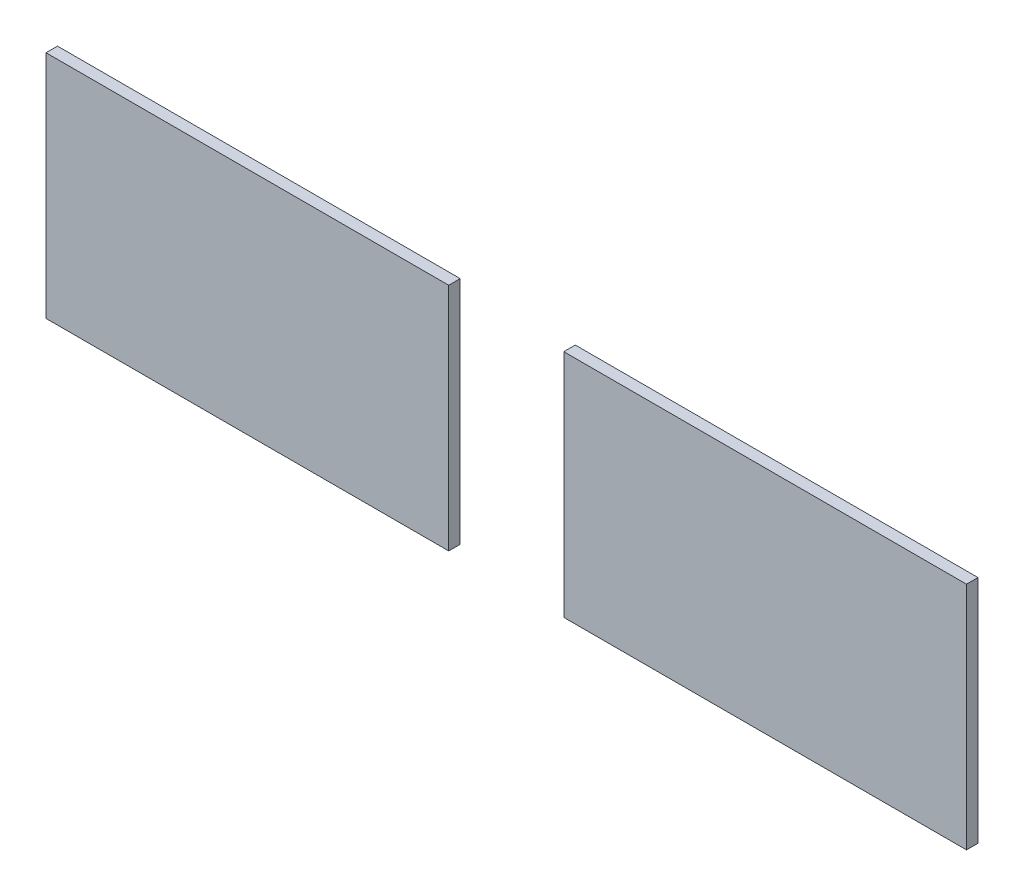
SolidWorks part; units mm, degrees
ref_plane "前视基准面" through (0, 0, 0) normal (0, 0, 1) x (1, 0, 0)
ref_plane "上视基准面" through (0, 0, 0) normal (0, 1, 0) x (1, 0, 0)
ref_plane "右视基准面" through (0, 0, 0) normal (1, 0, 0) x (0, 0, -1)
sketch "草图1" plane through (0, 0, 0) normal (0, 0, 1) x (1, 0, 0)
  line L1 (-0.8, 0.2) -> (-0.1, 0.2)
  line L2 (-0.8, 0.2) -> (-0.8, -0.2)
  line L3 (-0.8, -0.2) -> (-0.1, -0.2)
  line L4 (-0.1, 0.2) -> (-0.1, -0.2)
  line L5 (-0.8, 0.2) -> (-0.1, -0.2) construction
  line L6 (-0.8, -0.2) -> (-0.1, 0.2) construction
  line L7 (0.1, 0.2) -> (0.8, 0.2)
  line L8 (0.1, 0.2) -> (0.1, -0.2)
  line L9 (0.1, -0.2) -> (0.8, -0.2)
  line L10 (0.8, 0.2) -> (0.8, -0.2)
  line L11 (0.1, 0.2) -> (0.8, -0.2) construction
  line L12 (0.1, -0.2) -> (0.8, 0.2) construction
  point P0 (-0.45, 0)
  point P5 (0.45, 0)
  dimension "D1" = 0.2
  dimension "D2" = 0.7
  dimension "D3" = 0.2
  dimension "D4" = 0.7
extrude "凸台-拉伸1" add sketch "草图1" along normal blind 0.02
